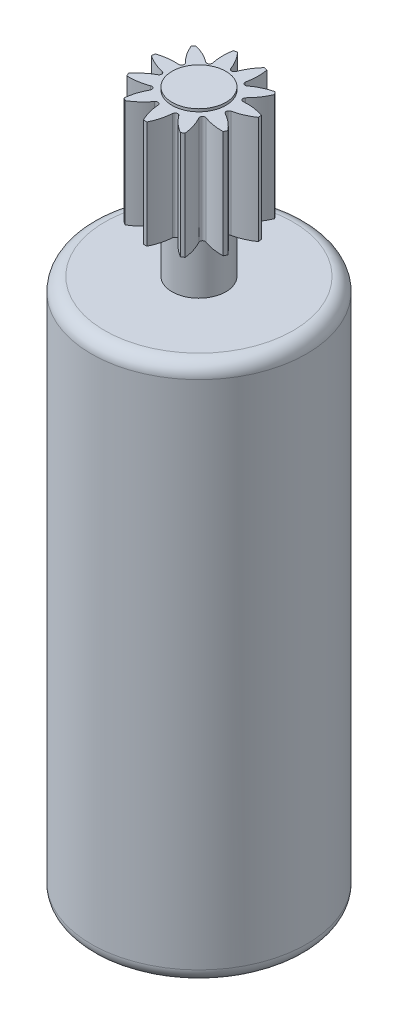
SolidWorks part; units mm, degrees
ref_plane "Front Plane" through (0, 0, 0) normal (0, 0, 1) x (1, 0, 0)
ref_plane "Top Plane" through (0, 0, 0) normal (0, 1, 0) x (1, 0, 0)
ref_plane "Right Plane" through (0, 0, 0) normal (1, 0, 0) x (0, 0, -1)
sketch "Sketch1" plane through (0, 0, 0) normal (0, 0, 1) x (1, 0, 0)
  line L0 (0, 13.05) -> (0, -13.05)
  line L1 (0, 13.05) -> (1, 13.05)
  line L2 (1, 13.05) -> (1, 12.95)
  line L3 (1, 12.95) -> (2, 12.95)
  line L4 (2, 12.95) -> (2, 8.95)
  line L5 (2, 8.95) -> (1, 8.95)
  line L6 (1, 8.95) -> (1, 6.95)
  line L7 (1, 6.95) -> (4, 6.95)
  line L8 (4, 6.95) -> (4, -13.05)
  line L9 (4, -13.05) -> (0, -13.05)
  point P11 (0, 0)
  point P12 (0, 0)
  dimension "D1" = 0.1
  dimension "D2" = 1
  dimension "D3" = 4
  dimension "D4" = 26.1
  dimension "D5" = 1
  dimension "D6" = 2
  dimension "D7" = 3
revolve "Revolve1" add sketch "Sketch1" angle 360 about L0
sketch "Sketch2" plane through (0, 12.95, 0) normal (0, 1, 0) x (1, 0, 0)
  line L0 (0, 0) -> (0, 5.445) construction
  line L1 (0, 2.9686) -> (-0.5, 3.9686) construction
  line L2 (0.5, 3.9686) -> (0, 2.9686) construction
  line L3 (0, 0) -> (2.9438, 4.5807) construction
  line L4 (0, 0) -> (4.953, 2.2619) construction
  line L5 (0, 0) -> (5.3896, -0.7749) construction
  line L6 (0, 0) -> (4.1151, -3.5657) construction
  line L7 (0, 0) -> (1.534, -5.2245) construction
  line L8 (0, 0) -> (-1.534, -5.2245) construction
  line L9 (0, 0) -> (-4.1151, -3.5657) construction
  line L10 (0, 0) -> (-5.3896, -0.7749) construction
  line L11 (0, 0) -> (-4.953, 2.2619) construction
  line L12 (0, 0) -> (-2.9438, 4.5807) construction
  line L13 (-0.5, 1.9365) -> (0, 0.9365) construction
  line L14 (0, 0.9365) -> (0.5, 1.9365) construction
  line L15 (0, 0) -> (2.9438, 4.5807) construction
  line L16 (0, 0) -> (4.953, 2.2619) construction
  line L17 (0, 0) -> (5.3896, -0.7749) construction
  line L18 (0, 0) -> (4.1151, -3.5657) construction
  line L19 (0, 0) -> (1.534, -5.2245) construction
  line L20 (0, 0) -> (-1.534, -5.2245) construction
  line L21 (0, 0) -> (-4.1151, -3.5657) construction
  line L22 (0, 0) -> (-5.3896, -0.7749) construction
  line L23 (0, 0) -> (-4.953, 2.2619) construction
  line L24 (0, 0) -> (-2.9438, 4.5807) construction
  circle A1 centre (0, 0) radius 2 construction
  arc A2 (0.5, 1.9365) -> (-0.5, 1.9365) centre (0, 0) ccw
  circle A4 centre (0, 0) radius 4 construction
  arc A8 (-0.5, 3.9686) -> (-0.0937, 3.3089) centre (-1.9676, 2.6098) cw construction
  arc A13 (0.5, 3.9686) -> (-0.5, 3.9686) centre (0, 0) ccw construction
  arc A14 (0.5, 3.9686) -> (0.0937, 3.3089) centre (1.9676, 2.6098) ccw construction
  arc A15 (0.0937, 3.3089) -> (-0.0937, 3.3089) centre (0, 3.3438) cw construction
  arc A16 (2.5662, 3.0683) -> (1.8677, 2.7329) centre (3.0662, 1.1318) ccw construction
  arc A17 (2.5662, 3.0683) -> (1.725, 3.6089) centre (0, 0) ccw construction
  arc A18 (1.725, 3.6089) -> (1.7101, 2.8343) centre (-0.2442, 3.2593) cw construction
  arc A19 (1.8677, 2.7329) -> (1.7101, 2.8343) centre (1.8078, 2.813) cw construction
  arc A20 (3.8177, 1.1938) -> (3.0488, 1.2893) centre (3.1914, -0.7056) ccw construction
  arc A21 (3.8177, 1.1938) -> (3.4023, 2.1034) centre (0, 0) ccw construction
  arc A22 (3.4023, 2.1034) -> (2.9709, 1.4598) centre (1.5566, 2.8739) cw construction
  arc A23 (3.0488, 1.2893) -> (2.9709, 1.4598) centre (3.0417, 1.3891) cw construction
  arc A24 (3.8571, -1.0597) -> (3.2619, -0.5636) centre (2.3033, -2.3189) ccw construction
  arc A25 (3.8571, -1.0597) -> (3.9994, -0.0699) centre (0, 0) ccw construction
  arc A26 (3.9994, -0.0699) -> (3.2885, -0.3782) centre (2.8633, 1.5761) cw construction
  arc A27 (3.2619, -0.5636) -> (3.2885, -0.3782) centre (3.3098, -0.4759) cw construction
  arc A28 (2.6719, -2.9768) -> (2.4393, -2.2377) centre (0.6839, -3.1961) ccw construction
  arc A29 (2.6719, -2.9768) -> (3.3267, -2.221) centre (0, 0) ccw construction
  arc A30 (3.3267, -2.221) -> (2.562, -2.096) centre (3.2609, -0.2221) cw construction
  arc A31 (2.4393, -2.2377) -> (2.562, -2.096) centre (2.5271, -2.1897) cw construction
  arc A32 (0.6383, -3.9487) -> (0.8423, -3.2012) centre (-1.1526, -3.0585) ccw construction
  arc A33 (0.6383, -3.9487) -> (1.5978, -3.667) centre (0, 0) ccw construction
  arc A34 (1.5978, -3.667) -> (1.0221, -3.1484) centre (2.6231, -1.9498) cw construction
  arc A35 (0.8423, -3.2012) -> (1.0221, -3.1484) centre (0.9421, -3.2084) cw construction
  arc A36 (-1.5978, -3.667) -> (-1.0221, -3.1484) centre (-2.6231, -1.9498) ccw construction
  arc A37 (-1.5978, -3.667) -> (-0.6383, -3.9487) centre (0, 0) ccw construction
  arc A38 (-0.6383, -3.9487) -> (-0.8423, -3.2012) centre (1.1526, -3.0585) cw construction
  arc A39 (-1.0221, -3.1484) -> (-0.8423, -3.2012) centre (-0.9421, -3.2084) cw construction
  arc A40 (-3.3267, -2.221) -> (-2.562, -2.096) centre (-3.2609, -0.2221) ccw construction
  arc A41 (-3.3267, -2.221) -> (-2.6719, -2.9768) centre (0, 0) ccw construction
  arc A42 (-2.6719, -2.9768) -> (-2.4393, -2.2377) centre (-0.6839, -3.1961) cw construction
  arc A43 (-2.562, -2.096) -> (-2.4393, -2.2377) centre (-2.5271, -2.1897) cw construction
  arc A44 (-3.9994, -0.0699) -> (-3.2885, -0.3782) centre (-2.8633, 1.5761) ccw construction
  arc A45 (-3.9994, -0.0699) -> (-3.8571, -1.0597) centre (0, 0) ccw construction
  arc A46 (-3.8571, -1.0597) -> (-3.2619, -0.5636) centre (-2.3033, -2.3189) cw construction
  arc A47 (-3.2885, -0.3782) -> (-3.2619, -0.5636) centre (-3.3098, -0.4759) cw construction
  arc A48 (-3.4023, 2.1034) -> (-2.9709, 1.4598) centre (-1.5566, 2.8739) ccw construction
  arc A49 (-3.4023, 2.1034) -> (-3.8177, 1.1938) centre (0, 0) ccw construction
  arc A50 (-3.8177, 1.1938) -> (-3.0488, 1.2893) centre (-3.1914, -0.7056) cw construction
  arc A51 (-2.9709, 1.4598) -> (-3.0488, 1.2893) centre (-3.0417, 1.3891) cw construction
  arc A52 (-1.725, 3.6089) -> (-1.7101, 2.8343) centre (0.2442, 3.2593) ccw construction
  arc A53 (-1.725, 3.6089) -> (-2.5662, 3.0683) centre (0, 0) ccw construction
  arc A54 (-2.5662, 3.0683) -> (-1.8677, 2.7329) centre (-3.0662, 1.1318) cw construction
  arc A55 (-1.7101, 2.8343) -> (-1.8677, 2.7329) centre (-1.8078, 2.813) cw construction
  arc A56 (-0.5, 1.9365) -> (-0.0937, 1.2767) centre (-1.9676, 0.5777) cw
  arc A57 (0.5, 1.9365) -> (0.0937, 1.2767) centre (1.9676, 0.5777) ccw
  arc A58 (0.0937, 1.2767) -> (-0.0937, 1.2767) centre (0, 1.3117) cw
  arc A59 (1.4676, 1.3588) -> (0.7691, 1.0234) centre (1.9675, -0.5777) ccw
  arc A60 (0.7691, 1.0234) -> (0.6114, 1.1247) centre (0.7092, 1.1035) cw
  arc A61 (0.6263, 1.8994) -> (0.6114, 1.1247) centre (-1.3429, 1.5497) cw
  arc A62 (1.4676, 1.3588) -> (0.6263, 1.8994) centre (0, 0) ccw
  arc A63 (1.9692, 0.3496) -> (1.2003, 0.4452) centre (1.3429, -1.5498) ccw
  arc A64 (1.2003, 0.4452) -> (1.1224, 0.6156) centre (1.1932, 0.5449) cw
  arc A65 (1.5538, 1.2593) -> (1.1224, 0.6156) centre (-0.2918, 2.0297) cw
  arc A66 (1.9692, 0.3496) -> (1.5538, 1.2593) centre (0, 0) ccw
  arc A67 (1.8456, -0.7705) -> (1.2504, -0.2744) centre (0.2918, -2.0297) ccw
  arc A68 (1.2504, -0.2744) -> (1.2771, -0.089) centre (1.2983, -0.1867) cw
  arc A69 (1.9879, 0.2193) -> (1.2771, -0.089) centre (0.8518, 1.8653) cw
  arc A70 (1.8456, -0.7705) -> (1.9879, 0.2193) centre (0, 0) ccw
  arc A71 (1.1361, -1.646) -> (0.9035, -0.9069) centre (-0.8519, -1.8653) ccw
  arc A72 (0.9035, -0.9069) -> (1.0263, -0.7653) centre (0.9913, -0.859) cw
  arc A73 (1.7909, -0.8903) -> (1.0263, -0.7653) centre (1.7251, 1.1087) cw
  arc A74 (1.1361, -1.646) -> (1.7909, -0.8903) centre (0, 0) ccw
  arc A75 (0.0658, -1.9989) -> (0.2698, -1.2514) centre (-1.7251, -1.1086) ccw
  arc A76 (0.2698, -1.2514) -> (0.4496, -1.1986) centre (0.3695, -1.2586) cw
  arc A77 (1.0253, -1.7172) -> (0.4496, -1.1986) centre (2.0506, 0) cw
  arc A78 (0.0658, -1.9989) -> (1.0253, -1.7172) centre (0, 0) ccw
  arc A79 (-1.0253, -1.7172) -> (-0.4496, -1.1986) centre (-2.0506, 0) ccw
  arc A80 (-0.4496, -1.1986) -> (-0.2698, -1.2514) centre (-0.3695, -1.2586) cw
  arc A81 (-0.0658, -1.9989) -> (-0.2698, -1.2514) centre (1.7251, -1.1086) cw
  arc A82 (-1.0253, -1.7172) -> (-0.0658, -1.9989) centre (0, 0) ccw
  arc A83 (-1.7909, -0.8903) -> (-1.0263, -0.7653) centre (-1.7251, 1.1087) ccw
  arc A84 (-1.0263, -0.7653) -> (-0.9035, -0.9069) centre (-0.9913, -0.859) cw
  arc A85 (-1.1361, -1.646) -> (-0.9035, -0.9069) centre (0.8519, -1.8653) cw
  arc A86 (-1.7909, -0.8903) -> (-1.1361, -1.646) centre (0, 0) ccw
  arc A87 (-1.9879, 0.2193) -> (-1.2771, -0.089) centre (-0.8518, 1.8653) ccw
  arc A88 (-1.2771, -0.089) -> (-1.2504, -0.2744) centre (-1.2983, -0.1867) cw
  arc A89 (-1.8456, -0.7705) -> (-1.2504, -0.2744) centre (-0.2918, -2.0297) cw
  arc A90 (-1.9879, 0.2193) -> (-1.8456, -0.7705) centre (0, 0) ccw
  arc A91 (-1.5538, 1.2593) -> (-1.1224, 0.6156) centre (0.2918, 2.0297) ccw
  arc A92 (-1.1224, 0.6156) -> (-1.2003, 0.4452) centre (-1.1932, 0.5449) cw
  arc A93 (-1.9692, 0.3496) -> (-1.2003, 0.4452) centre (-1.3429, -1.5498) cw
  arc A94 (-1.5538, 1.2593) -> (-1.9692, 0.3496) centre (0, 0) ccw
  arc A95 (-0.6263, 1.8994) -> (-0.6114, 1.1247) centre (1.3429, 1.5497) ccw
  arc A96 (-0.6114, 1.1247) -> (-0.7691, 1.0234) centre (-0.7092, 1.1035) cw
  arc A97 (-1.4676, 1.3588) -> (-0.7691, 1.0234) centre (-1.9675, -0.5777) cw
  arc A98 (-0.6263, 1.8994) -> (-1.4676, 1.3588) centre (0, 0) ccw
  point P3 (0, 2)
  point P14 (0, 4)
  point P97 (0, 0)
  point P186 (0, 0)
  dimension "D1" = 1
  dimension "D2" = 0.5
  dimension "D3" = 2
  dimension "D4" = 2
  dimension "D6" = 11
  dimension "D5" = 0.1
  dimension "D9" = 2
  dimension "D10" = 2
  dimension "D11" = 0.1
  dimension "D7" = 1
  dimension "D8" = 0.5
  dimension "D12" = 11
extrude "Cut-Extrude1" cut sketch "Sketch2" against normal up to surface (4 mm away) up to face at (-2, 8.95, 0)
fillet "Fillet1" radius 0.5 2 edges at (-4, -13.05, 0) (-4, 6.95, 0)
